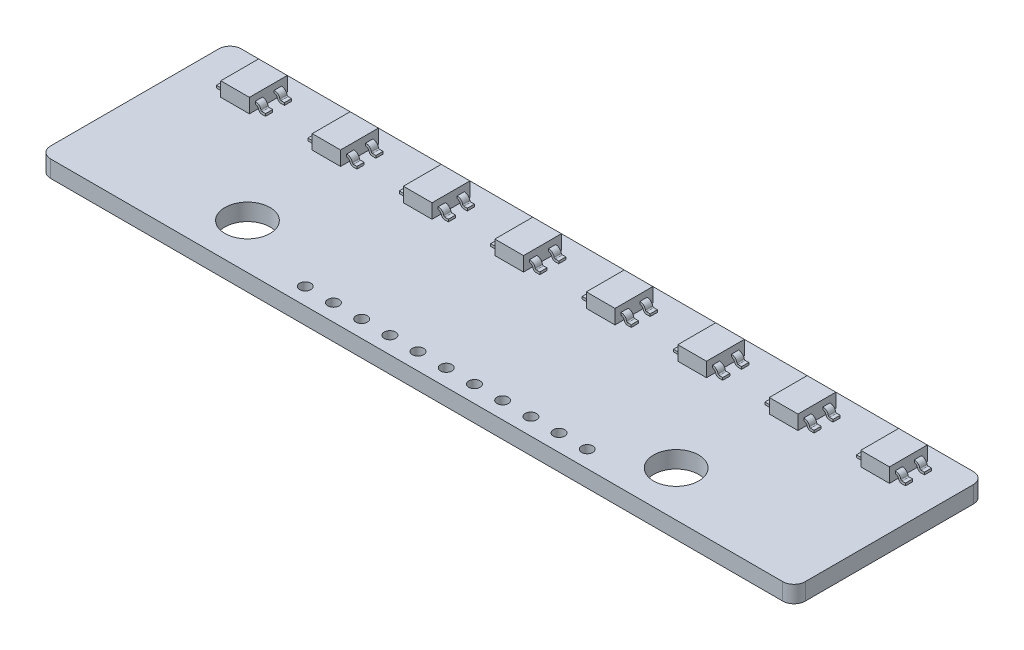
SolidWorks part; units mm, degrees
material "ABS"
ref_plane "Спереди" through (0, 0, 0) normal (0, 0, 1) x (1, 0, 0)
ref_plane "Сверху" through (0, 0, 0) normal (0, 1, 0) x (1, 0, 0)
ref_plane "Справа" through (0, 0, 0) normal (1, 0, 0) x (0, 0, -1)
sketch "Эскиз1" plane through (0, 0, 0) normal (0, 1, 0) x (1, 0, 0)
  line L0 (0, 11.0913) -> (0, -13.1273) construction
  line L1 (32.45, -8.45) -> (-32.45, -8.45)
  line L2 (33.45, -7.45) -> (33.45, 7.45)
  line L3 (32.45, 8.45) -> (-32.45, 8.45)
  line L4 (-33.45, -7.45) -> (-33.45, 7.45)
  line L5 (33.45, -8.45) -> (-33.45, 8.45) construction
  line L6 (33.45, 8.45) -> (-33.45, -8.45) construction
  arc A0 (33.45, 7.45) -> (32.45, 8.45) centre (32.45, 7.45) ccw
  arc A1 (32.45, -8.45) -> (33.45, -7.45) centre (32.45, -7.45) ccw
  arc A2 (-32.45, -8.45) -> (-33.45, -7.45) centre (-32.45, -7.45) cw
  arc A3 (-32.45, 8.45) -> (-33.45, 7.45) centre (-32.45, 7.45) ccw
  circle A4 centre (-19, -4.45) radius 2
  circle A5 centre (19, -4.45) radius 2
  circle A6 centre (-11.3789, -6.95) radius 0.5
  circle A7 centre (-8.8789, -6.95) radius 0.5
  circle A8 centre (-6.3789, -6.95) radius 0.5
  circle A9 centre (-3.8789, -6.95) radius 0.5
  circle A10 centre (-1.3789, -6.95) radius 0.5
  circle A11 centre (1.1211, -6.95) radius 0.5
  circle A12 centre (3.6211, -6.95) radius 0.5
  circle A13 centre (6.1211, -6.95) radius 0.5
  circle A14 centre (8.6211, -6.95) radius 0.5
  circle A15 centre (11.1211, -6.95) radius 0.5
  circle A16 centre (13.6211, -6.95) radius 0.5
  point P0 (0, 0)
  dimension "D3" = 1
  dimension "D4" = 4
  dimension "D6" = 1
  dimension "D1" = 66.9
  dimension "D2" = 16.9
  dimension "D5" = 38
  dimension "D8" = 1.5
  dimension "D9" = 4
  dimension "D7" = 11
extrude "Бобышка-Вытянуть1" add sketch "Эскиз1" along normal mid plane 1.5 contours L3 A3 L4 A2 L1 A1 L2 A0
sketch "Эскиз4" plane through (0, 0.75, 0) normal (0, 1, 0) x (1, 0, 0)
  line L0 (-33.45, 7.45) -> (-33.45, -7.45) construction
  line L1 (-27.1, 3.82) -> (-29.64, 3.82)
  line L2 (-27.1, 3.82) -> (-27.1, 7.18)
  line L3 (-27.1, 7.18) -> (-29.64, 7.18)
  line L4 (-29.64, 3.82) -> (-29.64, 7.18)
  line L5 (-27.1, 3.82) -> (-29.64, 7.18) construction
  line L6 (-27.1, 7.18) -> (-29.64, 3.82) construction
  line L7 (32.45, 8.45) -> (-32.45, 8.45) construction
  line L8 (-19.02, 3.82) -> (-21.53, 3.82)
  line L9 (-19.02, 3.82) -> (-19.02, 7.18)
  line L10 (-19.02, 7.18) -> (-21.53, 7.18)
  line L11 (-21.53, 3.82) -> (-21.53, 7.18)
  line L12 (-19.02, 3.82) -> (-21.53, 7.18) construction
  line L13 (-19.02, 7.18) -> (-21.53, 3.82) construction
  line L14 (-10.91, 3.82) -> (-13.45, 3.82)
  line L15 (-10.91, 3.82) -> (-10.91, 7.18)
  line L16 (-10.91, 7.18) -> (-13.45, 7.18)
  line L17 (-13.45, 3.82) -> (-13.45, 7.18)
  line L18 (-10.91, 3.82) -> (-13.45, 7.18) construction
  line L19 (-10.91, 7.18) -> (-13.45, 3.82) construction
  line L20 (-2.8, 3.82) -> (-5.34, 3.82)
  line L21 (-2.8, 3.82) -> (-2.8, 7.18)
  line L22 (-2.8, 7.18) -> (-5.34, 7.18)
  line L23 (-5.34, 3.82) -> (-5.34, 7.18)
  line L24 (-2.8, 3.82) -> (-5.34, 7.18) construction
  line L25 (-2.8, 7.18) -> (-5.34, 3.82) construction
  line L26 (5.31, 3.82) -> (2.77, 3.82)
  line L27 (5.31, 3.82) -> (5.31, 7.18)
  line L28 (5.31, 7.18) -> (2.77, 7.18)
  line L29 (2.77, 3.82) -> (2.77, 7.18)
  line L30 (5.31, 3.82) -> (2.77, 7.18) construction
  line L31 (5.31, 7.18) -> (2.77, 3.82) construction
  line L32 (13.42, 3.82) -> (10.88, 3.82)
  line L33 (13.42, 3.82) -> (13.42, 7.18)
  line L34 (13.42, 7.18) -> (10.88, 7.18)
  line L35 (10.88, 3.82) -> (10.88, 7.18)
  line L36 (13.42, 3.82) -> (10.88, 7.18) construction
  line L37 (13.42, 7.18) -> (10.88, 3.82) construction
  line L38 (21.53, 3.82) -> (18.99, 3.82)
  line L39 (21.53, 3.82) -> (21.53, 7.18)
  line L40 (21.53, 7.18) -> (18.99, 7.18)
  line L41 (18.99, 3.82) -> (18.99, 7.18)
  line L42 (21.53, 3.82) -> (18.99, 7.18) construction
  line L43 (21.53, 7.18) -> (18.99, 3.82) construction
  line L50 (29.64, 3.82) -> (27.1, 3.82)
  line L51 (29.64, 3.82) -> (29.64, 7.18)
  line L52 (29.64, 7.18) -> (27.1, 7.18)
  line L53 (27.1, 3.82) -> (27.1, 7.18)
  line L54 (29.64, 3.82) -> (27.1, 7.18) construction
  line L55 (29.64, 7.18) -> (27.1, 3.82) construction
  line L56 (33.45, -7.45) -> (33.45, 7.45) construction
  point P0 (-28.37, 5.5)
  point P9 (-20.275, 5.5)
  point P14 (-12.18, 5.5)
  point P19 (-4.07, 5.5)
  point P24 (4.04, 5.5)
  point P29 (12.15, 5.5)
  point P34 (20.26, 5.5)
  point P44 (28.37, 5.5)
  dimension "D1" = 2.54
  dimension "D2" = 3.36
  dimension "D3" = 3.81
  dimension "D4" = 1.27
  dimension "D5" = 5.57
  dimension "D6" = 5.57
  dimension "D7" = 5.57
  dimension "D8" = 5.57
  dimension "D9" = 5.57
  dimension "D10" = 5.57
  dimension "D13" = 3.81
  dimension "D14" = 2.54
  dimension "D16" = 2.54
  dimension "D17" = 2.54
  dimension "D18" = 2.54
  dimension "D19" = 2.54
  dimension "D20" = 2.54
  dimension "D11" = 5.57
extrude "Бобышка-Вытянуть2" add sketch "Эскиз4" along normal blind 1.27 separate body
ref_plane "Плоскость1" through (0, 0, -5.5) normal (0, 0, -1) x (-1, 0, 0)
ref_plane "Плоскость2" through (0, 0, -6.34) normal (0, 0, -1) x (-1, 0, 0)
sketch "Эскиз5" plane through (0, 0, -6.34) normal (0, 0, -1) x (-1, 0, 0)
  line L0 (29.64, 1.4583) -> (29.64, 1.25)
  line L1 (29.64, 2.02) -> (29.64, 0.75) construction
  line L2 (32.45, 0.75) -> (-32.45, 0.75) construction
  line L4 (28.37, 2.02) -> (28.37, 0.3466) construction
  line L5 (29.64, 2.02) -> (27.1, 2.02) construction
  line L9 (30.2343, 0.75) -> (30.5472, 0.75)
  line L10 (30.5472, 0.75) -> (30.5472, 0.96)
  line L11 (30.5472, 0.96) -> (30.2343, 0.96)
  line L12 (26.1928, 0.96) -> (26.5057, 0.96)
  line L13 (26.1928, 0.75) -> (26.1928, 0.96)
  line L14 (26.5057, 0.75) -> (26.1928, 0.75)
  line L15 (27.1, 1.4583) -> (27.1, 1.25)
  arc A4 (29.64, 1.25) -> (29.9325, 0.9868) centre (29.593, 0.9037) cw
  arc A5 (29.9325, 0.9868) -> (30.2343, 0.75) centre (30.2343, 1.0607) ccw
  arc A6 (30.2343, 0.96) -> (30.1351, 1.0431) centre (30.2343, 1.0607) cw
  arc A7 (30.1351, 1.0431) -> (29.64, 1.4583) centre (29.64, 0.9554) ccw
  arc A8 (26.6049, 1.0431) -> (27.1, 1.4583) centre (27.1, 0.9554) cw
  arc A9 (26.5057, 0.96) -> (26.6049, 1.0431) centre (26.5057, 1.0607) ccw
  arc A10 (26.8075, 0.9868) -> (26.5057, 0.75) centre (26.5057, 1.0607) cw
  arc A11 (27.1, 1.25) -> (26.8075, 0.9868) centre (27.147, 0.9037) ccw
  point P12 (29.64, 0.75)
  point P42 (27.1, 0.75)
  dimension "D1" = 0.21
  dimension "D3" = 0.5
  dimension "D2" = 0.2083
extrude "Бобышка-Вытянуть3" add sketch "Эскиз5" along normal mid plane 0.635 separate body
mirror "Зеркальное отражение1" about plane through (0, 0, -5.5) normal (0, 0, -1) of "Бобышка-Вытянуть3"
pattern_linear "Линейный массив3" count 8 spacing 8.105 along (1, 0, 0) of "Зеркальное отражение1", "Бобышка-Вытянуть3"
equation "\"D6@Эскиз4\"=\"D5@Эскиз4\""
equation "\"D7@Эскиз4\"=\"D5@Эскиз4\""
equation "\"D13@Эскиз4\"=\"D3@Эскиз4\""
equation "\"D14@Эскиз4\"=\"D1@Эскиз4\""
equation "\"D16@Эскиз4\"=\"D1@Эскиз4\""
equation "\"D8@Эскиз4\"=\"D5@Эскиз4\""
equation "\"D9@Эскиз4\"=\"D5@Эскиз4\""
equation "\"D10@Эскиз4\"=\"D5@Эскиз4\""
equation "\"D11@Эскиз4\"=\"D5@Эскиз4\""
